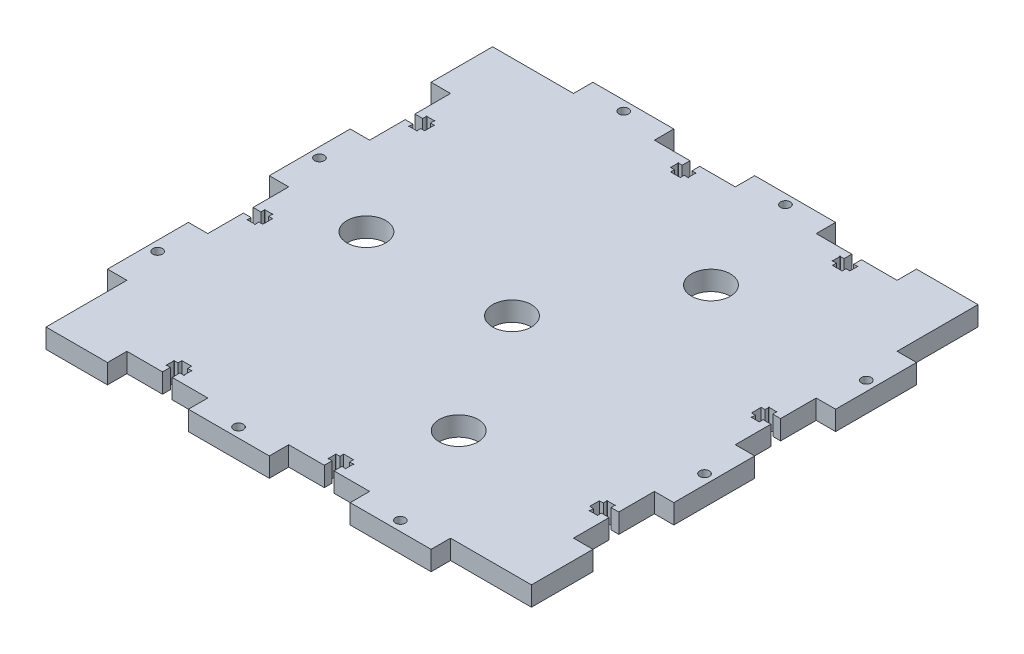
SolidWorks part; units mm, degrees
ref_plane "Front Plane" through (0, 0, 0) normal (0, 0, 1) x (1, 0, 0)
ref_plane "Top Plane" through (0, 0, 0) normal (0, 1, 0) x (1, 0, 0)
ref_plane "Right Plane" through (0, 0, 0) normal (1, 0, 0) x (0, 0, -1)
sketch "Sketch1" plane through (0, 0, 0) normal (0, 1, 0) x (1, 0, 0)
  line L0 (0, 75) -> (25, 75)
  line L1 (-50, 75) -> (-25, 75)
  line L2 (-75, 69) -> (-75, 50)
  line L3 (-69, -75) -> (-50, -75)
  line L4 (75, 50) -> (75, 25)
  line L7 (-75, 69) -> (-50, 69)
  line L8 (-50, 75) -> (-50, 69)
  line L10 (-25, 75) -> (-25, 69)
  line L11 (-25, 69) -> (0, 69)
  line L12 (0, 75) -> (0, 69)
  line L13 (50, 75) -> (69, 75)
  line L15 (25, 75) -> (25, 69)
  line L16 (25, 69) -> (50, 69)
  line L17 (50, 75) -> (50, 69)
  line L18 (75, 0) -> (75, -25)
  line L21 (75, 50) -> (69, 50)
  line L22 (69, 75) -> (69, 50)
  line L23 (75, 25) -> (69, 25)
  line L25 (75, 0) -> (69, 0)
  line L26 (69, 25) -> (69, 0)
  line L27 (75, -25) -> (69, -25)
  line L29 (75, -50) -> (69, -50)
  line L30 (69, -25) -> (69, -50)
  line L31 (75, -50) -> (75, -69)
  line L32 (25, -75) -> (50, -75)
  line L35 (75, -69) -> (50, -69)
  line L36 (50, -75) -> (50, -69)
  line L38 (25, -75) -> (25, -69)
  line L39 (25, -69) -> (0, -69)
  line L40 (0, -75) -> (0, -69)
  line L42 (-25, -75) -> (-25, -69)
  line L43 (-25, -69) -> (-50, -69)
  line L44 (-50, -75) -> (-50, -69)
  line L45 (-25, -75) -> (0, -75)
  line L46 (-75, 25) -> (-75, 0)
  line L49 (-75, -50) -> (-69, -50)
  line L50 (-69, -75) -> (-69, -50)
  line L51 (-75, -25) -> (-69, -25)
  line L53 (-75, 0) -> (-69, 0)
  line L54 (-69, -25) -> (-69, 0)
  line L55 (-75, 25) -> (-69, 25)
  line L57 (-75, 50) -> (-69, 50)
  line L58 (-69, 25) -> (-69, 50)
  line L59 (-75, -25) -> (-75, -50)
  dimension "D1" = 150
  dimension "D2" = 150
  dimension "D3" = 25
  dimension "D4" = 6
  dimension "D5" = 25
  dimension "25" = 25
  dimension "D6" = 25
  dimension "D7" = 6
  dimension "D8" = 6
  dimension "D9" = 25
  dimension "D10" = 25
  dimension "D11" = 6
  dimension "D12" = 25
  dimension "D13" = 6
  dimension "D14" = 25
  dimension "D15" = 25
  dimension "D16" = 6
  dimension "D17" = 25
  dimension "D18" = 19
  dimension "D19" = 6
  dimension "D20" = 25
  dimension "D21" = 25
  dimension "D22" = 25
  dimension "D23" = 6
  dimension "D24" = 6
  dimension "D25" = 25
  dimension "D26" = 25
  dimension "D27" = 19
  dimension "D28" = 6
  dimension "D29" = 25
  dimension "D30" = 25
  dimension "D31" = 6
  dimension "D32" = 25
  dimension "D33" = 25
  dimension "D34" = 6
  dimension "D35" = 25
  dimension "D36" = 19
extrude "Boss-Extrude1" add sketch "Sketch1" along normal blind 6
sketch "Sketch2" plane through (0, 6, 0) normal (0, 1, 0) x (1, 0, 0)
  line L0 (-25, 75) -> (-50, 75) construction
  line L1 (-25, 69) -> (-25, 75) construction
  line L2 (25, 75) -> (0, 75) construction
  line L3 (25, 69) -> (25, 75) construction
  line L4 (75, 25) -> (75, 50) construction
  line L5 (75, 50) -> (69, 50) construction
  line L6 (75, -25) -> (75, 0) construction
  line L7 (75, 0) -> (69, 0) construction
  line L8 (25, -75) -> (50, -75) construction
  line L9 (50, -75) -> (50, -69) construction
  line L10 (-25, -75) -> (0, -75) construction
  line L11 (0, -75) -> (0, -69) construction
  line L12 (-69, -25) -> (-75, -25) construction
  line L13 (-75, -25) -> (-75, -50) construction
  line L14 (-75, 25) -> (-75, 0) construction
  line L15 (-75, 0) -> (-69, 0) construction
  line L16 (-11, 69) -> (-14, 69)
  line L59 (0, 69) -> (-25, 69) construction
  line L60 (-14, 69) -> (-14, 66.6)
  line L61 (-14, 66.6) -> (-15.1, 66.6)
  line L63 (-15.2, 66.5) -> (-15.2, 64.3)
  line L65 (-15.1, 64.2) -> (-14, 64.2)
  line L66 (-14, 64.2) -> (-14, 63)
  line L67 (-14, 63) -> (-11, 63)
  line L69 (-12.5, 69) -> (-12.5, 63) construction
  line L72 (-11, 64.2) -> (-11, 63)
  line L73 (-9.9, 64.2) -> (-11, 64.2)
  line L74 (-9.8, 66.5) -> (-9.8, 64.3)
  line L75 (-11, 66.6) -> (-9.9, 66.6)
  line L76 (-11, 69) -> (-11, 66.6)
  line L91 (69, 11) -> (69, 14)
  line L92 (69, 14) -> (66.6, 14)
  line L93 (66.6, 14) -> (66.6, 15.1)
  line L94 (66.5, 15.2) -> (64.3, 15.2)
  line L95 (64.2, 15.1) -> (64.2, 14)
  line L96 (64.2, 14) -> (63, 14)
  line L97 (63, 14) -> (63, 11)
  line L98 (69, 12.5) -> (63, 12.5) construction
  line L99 (64.2, 11) -> (63, 11)
  line L100 (64.2, 9.9) -> (64.2, 11)
  line L101 (66.5, 9.8) -> (64.3, 9.8)
  line L102 (66.6, 11) -> (66.6, 9.9)
  line L103 (69, 11) -> (66.6, 11)
  line L104 (69, 0) -> (69, 25) construction
  line L105 (39, 69) -> (36, 69)
  line L106 (36, 69) -> (36, 66.6)
  line L107 (36, 66.6) -> (34.9, 66.6)
  line L108 (34.8, 66.5) -> (34.8, 64.3)
  line L109 (34.9, 64.2) -> (36, 64.2)
  line L110 (36, 64.2) -> (36, 63)
  line L111 (36, 63) -> (39, 63)
  line L112 (37.5, 69) -> (37.5, 63) construction
  line L113 (39, 64.2) -> (39, 63)
  line L114 (40.1, 64.2) -> (39, 64.2)
  line L115 (40.2, 66.5) -> (40.2, 64.3)
  line L116 (39, 66.6) -> (40.1, 66.6)
  line L117 (39, 69) -> (39, 66.6)
  line L118 (50, 69) -> (25, 69) construction
  line L119 (69, -39) -> (69, -36)
  line L120 (69, -36) -> (66.6, -36)
  line L121 (66.6, -36) -> (66.6, -34.9)
  line L122 (66.5, -34.8) -> (64.3, -34.8)
  line L123 (64.2, -34.9) -> (64.2, -36)
  line L124 (64.2, -36) -> (63, -36)
  line L125 (63, -36) -> (63, -39)
  line L126 (69, -37.5) -> (63, -37.5) construction
  line L127 (64.2, -39) -> (63, -39)
  line L128 (64.2, -40.1) -> (64.2, -39)
  line L129 (66.5, -40.2) -> (64.3, -40.2)
  line L130 (66.6, -39) -> (66.6, -40.1)
  line L131 (69, -39) -> (66.6, -39)
  line L132 (69, -50) -> (69, -25) construction
  line L133 (11, -69) -> (14, -69)
  line L134 (14, -69) -> (14, -66.6)
  line L135 (14, -66.6) -> (15.1, -66.6)
  line L136 (15.2, -66.5) -> (15.2, -64.3)
  line L137 (15.1, -64.2) -> (14, -64.2)
  line L138 (14, -64.2) -> (14, -63)
  line L139 (14, -63) -> (11, -63)
  line L140 (12.5, -69) -> (12.5, -63) construction
  line L141 (11, -64.2) -> (11, -63)
  line L142 (9.9, -64.2) -> (11, -64.2)
  line L143 (9.8, -66.5) -> (9.8, -64.3)
  line L144 (11, -66.6) -> (9.9, -66.6)
  line L145 (11, -69) -> (11, -66.6)
  line L146 (0, -69) -> (25, -69) construction
  line L147 (-39, -69) -> (-36, -69)
  line L148 (-36, -69) -> (-36, -66.6)
  line L149 (-36, -66.6) -> (-34.9, -66.6)
  line L150 (-34.8, -66.5) -> (-34.8, -64.3)
  line L151 (-34.9, -64.2) -> (-36, -64.2)
  line L152 (-36, -64.2) -> (-36, -63)
  line L153 (-36, -63) -> (-39, -63)
  line L154 (-37.5, -69) -> (-37.5, -63) construction
  line L155 (-39, -64.2) -> (-39, -63)
  line L156 (-40.1, -64.2) -> (-39, -64.2)
  line L157 (-40.2, -66.5) -> (-40.2, -64.3)
  line L158 (-39, -66.6) -> (-40.1, -66.6)
  line L159 (-39, -69) -> (-39, -66.6)
  line L160 (-50, -69) -> (-25, -69) construction
  line L161 (-69, 39) -> (-69, 36)
  line L162 (-69, 36) -> (-66.6, 36)
  line L163 (-66.6, 36) -> (-66.6, 34.9)
  line L164 (-66.5, 34.8) -> (-64.3, 34.8)
  line L165 (-64.2, 34.9) -> (-64.2, 36)
  line L166 (-64.2, 36) -> (-63, 36)
  line L167 (-63, 36) -> (-63, 39)
  line L168 (-69, 37.5) -> (-63, 37.5) construction
  line L169 (-64.2, 39) -> (-63, 39)
  line L170 (-64.2, 40.1) -> (-64.2, 39)
  line L171 (-66.5, 40.2) -> (-64.3, 40.2)
  line L172 (-66.6, 39) -> (-66.6, 40.1)
  line L173 (-69, 39) -> (-66.6, 39)
  line L174 (-69, 50) -> (-69, 25) construction
  line L175 (-69, -11) -> (-69, -14)
  line L176 (-69, -14) -> (-66.6, -14)
  line L177 (-66.6, -14) -> (-66.6, -15.1)
  line L178 (-66.5, -15.2) -> (-64.3, -15.2)
  line L179 (-64.2, -15.1) -> (-64.2, -14)
  line L180 (-64.2, -14) -> (-63, -14)
  line L181 (-63, -14) -> (-63, -11)
  line L182 (-69, -12.5) -> (-63, -12.5) construction
  line L183 (-64.2, -11) -> (-63, -11)
  line L184 (-64.2, -9.9) -> (-64.2, -11)
  line L185 (-66.5, -9.8) -> (-64.3, -9.8)
  line L186 (-66.6, -11) -> (-66.6, -9.9)
  line L187 (-69, -11) -> (-66.6, -11)
  line L188 (-69, 0) -> (-69, -25) construction
  circle A0 centre (-37.5, 72) radius 1.5
  circle A1 centre (12.5, 72) radius 1.5
  circle A2 centre (72, 37.5) radius 1.5
  circle A3 centre (72, -12.5) radius 1.5
  circle A4 centre (37.5, -72) radius 1.5
  circle A5 centre (-12.5, -72) radius 1.5
  circle A6 centre (-72, -37.5) radius 1.5
  circle A7 centre (-72, 12.5) radius 1.5
  arc A9 (-15.1, 66.6) -> (-15.2, 66.5) centre (-15.2, 66.6) ccw
  arc A10 (-15.2, 64.3) -> (-15.1, 64.2) centre (-15.2, 64.2) ccw
  arc A11 (-9.8, 64.3) -> (-9.9, 64.2) centre (-9.8, 64.2) cw
  arc A12 (-9.9, 66.6) -> (-9.8, 66.5) centre (-9.8, 66.6) cw
  arc A17 (66.6, 15.1) -> (66.5, 15.2) centre (66.6, 15.2) ccw
  arc A18 (64.3, 15.2) -> (64.2, 15.1) centre (64.2, 15.2) ccw
  arc A19 (64.3, 9.8) -> (64.2, 9.9) centre (64.2, 9.8) cw
  arc A20 (66.6, 9.9) -> (66.5, 9.8) centre (66.6, 9.8) cw
  arc A21 (34.9, 66.6) -> (34.8, 66.5) centre (34.8, 66.6) ccw
  arc A22 (34.8, 64.3) -> (34.9, 64.2) centre (34.8, 64.2) ccw
  arc A23 (40.2, 64.3) -> (40.1, 64.2) centre (40.2, 64.2) cw
  arc A24 (40.1, 66.6) -> (40.2, 66.5) centre (40.2, 66.6) cw
  arc A25 (66.6, -34.9) -> (66.5, -34.8) centre (66.6, -34.8) ccw
  arc A26 (64.3, -34.8) -> (64.2, -34.9) centre (64.2, -34.8) ccw
  arc A27 (64.3, -40.2) -> (64.2, -40.1) centre (64.2, -40.2) cw
  arc A28 (66.6, -40.1) -> (66.5, -40.2) centre (66.6, -40.2) cw
  arc A29 (15.1, -66.6) -> (15.2, -66.5) centre (15.2, -66.6) ccw
  arc A30 (15.2, -64.3) -> (15.1, -64.2) centre (15.2, -64.2) ccw
  arc A31 (9.8, -64.3) -> (9.9, -64.2) centre (9.8, -64.2) cw
  arc A32 (9.9, -66.6) -> (9.8, -66.5) centre (9.8, -66.6) cw
  arc A33 (-34.9, -66.6) -> (-34.8, -66.5) centre (-34.8, -66.6) ccw
  arc A34 (-34.8, -64.3) -> (-34.9, -64.2) centre (-34.8, -64.2) ccw
  arc A35 (-40.2, -64.3) -> (-40.1, -64.2) centre (-40.2, -64.2) cw
  arc A36 (-40.1, -66.6) -> (-40.2, -66.5) centre (-40.2, -66.6) cw
  arc A37 (-66.6, 34.9) -> (-66.5, 34.8) centre (-66.6, 34.8) ccw
  arc A38 (-64.3, 34.8) -> (-64.2, 34.9) centre (-64.2, 34.8) ccw
  arc A39 (-64.3, 40.2) -> (-64.2, 40.1) centre (-64.2, 40.2) cw
  arc A40 (-66.6, 40.1) -> (-66.5, 40.2) centre (-66.6, 40.2) cw
  arc A41 (-66.6, -15.1) -> (-66.5, -15.2) centre (-66.6, -15.2) ccw
  arc A42 (-64.3, -15.2) -> (-64.2, -15.1) centre (-64.2, -15.2) ccw
  arc A43 (-64.3, -9.8) -> (-64.2, -9.9) centre (-64.2, -9.8) cw
  arc A44 (-66.6, -9.9) -> (-66.5, -9.8) centre (-66.6, -9.8) cw
  point P83 (-12.5, 69)
  point P104 (69, 12.5)
  point P122 (37.5, 69)
  point P148 (69, -37.5)
  point P174 (12.5, -69)
  point P196 (-37.5, -69)
  point P222 (-69, 37.5)
  point P246 (-69, -12.5)
  dimension "D1" = 3
  dimension "D3" = 3
  dimension "D5" = 3
  dimension "D7" = 3
  dimension "D9" = 3
  dimension "D11" = 3
  dimension "D13" = 12.5
  dimension "D15" = 3
  dimension "D32" = 3
  dimension "D31" = 3
  dimension "D17" = 3
  dimension "D29" = 3
  dimension "D30" = 3
  dimension "D33" = 3
  dimension "D34" = 3
  dimension "D35" = 3
  dimension "D36" = 3
  dimension "D2" = 12.5
  dimension "D4" = 12.5
  dimension "D6" = 12.5
  dimension "D8" = 12.5
  dimension "D10" = 12.5
  dimension "D12" = 12.5
  dimension "D14" = 3
  dimension "D16" = 12.5
  dimension "D18" = 6
  dimension "D19" = 5.4
  dimension "D20" = 2.4
  dimension "D21" = 1.2
  dimension "D22" = 0.1
  dimension "D23" = 3
  dimension "D24" = 6
  dimension "D25" = 5.4
  dimension "D26" = 2.4
  dimension "D27" = 1.2
  dimension "D28" = 0.1
  dimension "D37" = 3
  dimension "D38" = 6
  dimension "D39" = 5.4
  dimension "D40" = 2.4
  dimension "D41" = 1.2
  dimension "D42" = 0.1
  dimension "D43" = 3
  dimension "D44" = 6
  dimension "D45" = 5.4
  dimension "D46" = 2.4
  dimension "D47" = 1.2
  dimension "D48" = 0.1
  dimension "D49" = 3
  dimension "D50" = 6
  dimension "D51" = 5.4
  dimension "D52" = 2.4
  dimension "D53" = 1.2
  dimension "D54" = 0.1
  dimension "D55" = 3
  dimension "D56" = 6
  dimension "D57" = 5.4
  dimension "D58" = 2.4
  dimension "D59" = 1.2
  dimension "D60" = 0.1
  dimension "D61" = 3
  dimension "D62" = 6
  dimension "D63" = 5.4
  dimension "D64" = 2.4
  dimension "D65" = 1.2
  dimension "D66" = 0.1
  dimension "D67" = 3
  dimension "D68" = 6
  dimension "D69" = 5.4
  dimension "D70" = 2.4
  dimension "D71" = 1.2
  dimension "D72" = 0.1
extrude "Cut-Extrude1" cut sketch "Sketch2" against normal through all
sketch "Sketch3" plane through (0, 0, 0) normal (0, -1, 0) x (1, 0, 0)
  line L0 (69, 0) -> (-69, 0) construction
  circle A0 centre (0, 0) radius 6
  circle A1 centre (-45, 0) radius 6
  dimension "D2" = 45
extrude "Cut-Extrude2" cut sketch "Sketch3" against normal through all
pattern_circular "CirPattern1" count 3 over 360 about axis through (0, 0, 0) along (0, 1, 0) of "Cut-Extrude2"
